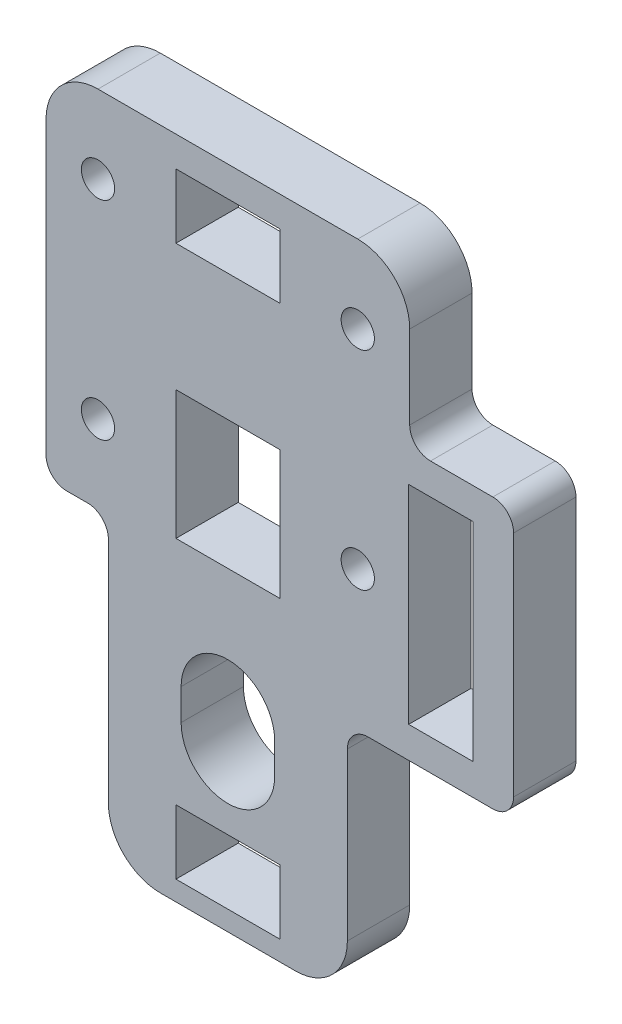
SolidWorks part; units mm, degrees
ref_plane "Front Plane" through (0, 0, 0) normal (0, 0, 1) x (1, 0, 0)
ref_plane "Top Plane" through (0, 0, 0) normal (0, 1, 0) x (1, 0, 0)
ref_plane "Right Plane" through (0, 0, 0) normal (1, 0, 0) x (0, 0, -1)
sketch "Sketch1" plane through (0, 0, 0) normal (0, 0, 1) x (1, 0, 0)
  line L0 (-5, -6.3) -> (5, -6.3)
  line L1 (-12.5, -12.5) -> (12.5, -12.5) construction
  line L2 (-12.5, -12.5) -> (-12.5, 7.5) construction
  line L3 (-12.5, 7.5) -> (12.5, 7.5) construction
  line L4 (12.5, -12.5) -> (12.5, 7.5) construction
  line L5 (-12.5, -12.5) -> (12.5, 7.5) construction
  line L6 (-12.5, 7.5) -> (12.5, -12.5) construction
  line L7 (17.5, -20) -> (11.5, -20)
  line L8 (17.5, -20) -> (17.5, 15)
  line L9 (17.5, 15) -> (-17.5, 15)
  line L10 (-17.5, -20) -> (-17.5, 15)
  line L11 (17.5, -20) -> (-17.5, 15) construction
  line L12 (17.5, 15) -> (-17.5, -20) construction
  line L13 (-5, 12.1) -> (5, 12.1)
  line L14 (-5, 12.1) -> (-5, 5.9)
  line L15 (-5, 5.9) -> (5, 5.9)
  line L16 (5, 12.1) -> (5, 5.9)
  line L17 (-5, 12.1) -> (5, 5.9) construction
  line L18 (-5, 5.9) -> (5, 12.1) construction
  line L19 (-5, -6.3) -> (-5, -18.7)
  line L20 (-5, -18.7) -> (5, -18.7)
  line L21 (5, -6.3) -> (5, -18.7)
  line L22 (-5, -6.3) -> (5, -18.7) construction
  line L23 (-5, -18.7) -> (5, -6.3) construction
  line L24 (0, 24.9943) -> (0, -49) construction
  line L25 (-11.5, -20) -> (-17.5, -20)
  line L26 (-11.5, -49) -> (11.5, -49)
  line L27 (-11.5, -49) -> (-11.5, -20)
  line L29 (11.5, -49) -> (11.5, -20)
  line L30 (-11.5, -49) -> (11.5, -20) construction
  line L31 (-11.5, -20) -> (11.5, -49) construction
  line L32 (0, -33.8) -> (0, -30.8) construction
  line L33 (-4.5, -33.8) -> (-4.5, -30.8)
  line L34 (4.5, -33.8) -> (4.5, -30.8)
  line L35 (-5, -40.9) -> (5, -40.9)
  line L36 (-5, -40.9) -> (-5, -47.1)
  line L37 (-5, -47.1) -> (5, -47.1)
  line L38 (5, -40.9) -> (5, -47.1)
  line L39 (-5, -40.9) -> (5, -47.1) construction
  line L40 (-5, -47.1) -> (5, -40.9) construction
  circle A0 centre (12.5, 7.5) radius 1.6
  circle A1 centre (-12.5, 7.5) radius 1.6
  circle A2 centre (-12.5, -12.5) radius 1.6
  circle A3 centre (12.5, -12.5) radius 1.6
  arc A4 (-4.5, -33.8) -> (4.5, -33.8) centre (0, -33.8) ccw
  arc A5 (4.5, -30.8) -> (-4.5, -30.8) centre (0, -30.8) ccw
  point P0 (0, -2.5)
  point P7 (0, 9)
  point P9 (0, -2.5)
  point P24 (0, -12.5)
  point P29 (0, -32.3)
  point P31 (0, -34.5)
  point P46 (0, -44)
  dimension "D3" = 3.2
  dimension "D15" = 4.5
  dimension "D1" = 25
  dimension "D2" = 20
  dimension "D4" = 35
  dimension "D5" = 35
  dimension "D6" = 6
  dimension "D7" = 10
  dimension "D8" = 6.2
  dimension "D9" = 10
  dimension "D10" = 12.4
  dimension "D12" = 23
  dimension "D13" = 29
  dimension "D14" = 47.3
  dimension "D16" = 3
  dimension "D17" = 10
  dimension "D18" = 6.2
  dimension "D19" = 5
extrude "Boss-Extrude1" add sketch "Sketch1" along normal blind 6
sketch "Sketch4" plane through (17.5, 0, 0) normal (1, 0, 0) x (0, 0, -1)
  line L0 (0, 0) -> (-6, 0)
  line L4 (0, -20) -> (0, 15)
  line L5 (0, 15) -> (-6, 15)
  line L6 (-6, 15) -> (-6, -20)
  line L7 (-6, -20) -> (0, -20)
  line L8 (0, -20) -> (0, 0)
  line L10 (-6, 0) -> (-6, -20)
  line L11 (-6, -20) -> (0, -20)
  dimension "D2" = 20
  dimension "D1" = 0
extrude "Boss-Extrude2" add sketch "Sketch4" along normal blind 10
sketch "Sketch7" plane through (11.5, 0, 0) normal (1, 0, 0) x (0, 0, -1)
  line L0 (-6, -26) -> (0, -26)
  line L1 (-6, -49) -> (-6, -20) construction
  line L2 (0, -49) -> (0, -20) construction
  line L7 (-6, -20) -> (-6, -49)
  line L8 (-6, -49) -> (0, -49)
  line L9 (0, -49) -> (0, -20)
  line L10 (0, -20) -> (-6, -20)
  line L11 (-6, -20) -> (-6, -26)
  line L13 (0, -26) -> (0, -20)
  line L14 (0, -20) -> (-6, -20)
  line L15 (-6, -49) -> (0, -49)
  line M6 (-6, -20) -> (-6, -49)
  line M8 (0, -49) -> (0, -20)
  line M9 (0, -20) -> (-6, -20)
  dimension "D2" = 6
  dimension "D1" = 0
extrude "Boss-Extrude3" add sketch "Sketch7" along normal up to surface (16 mm away) contours L0 M6 M8 M9 up to face at (27.5, -10, 3)
sketch "Sketch6" plane through (0, 0, 6) normal (0, 0, 1) x (1, 0, 0)
  line L0 (27.5, -13) -> (-17.5, -13) construction
  line L1 (17.4, -3) -> (23.6, -3)
  line L2 (17.4, -3) -> (17.4, -23)
  line L3 (17.4, -23) -> (23.6, -23)
  line L4 (23.6, -3) -> (23.6, -23)
  line L5 (17.4, -3) -> (23.6, -23) construction
  line L6 (17.4, -23) -> (23.6, -3) construction
  line L7 (27.5, 0) -> (27.5, -26) construction
  line L8 (-17.5, 15) -> (-17.5, -20) construction
  line L10 (12.5, 7.5) -> (12.5, -12.5) construction
  point P0 (20.5, -13)
  point P11 (0, 0)
  point P16 (0, 0)
  point P17 (0, 0)
  point P18 (0, 0)
  point P19 (0, 0)
  point P20 (0, 0)
  dimension "D1" = 6.2
  dimension "D2" = 20
  dimension "D3" = 8
extrude "Cut-Extrude1" cut sketch "Sketch6" against normal up to next
fillet "Fillet1" radius 2 6 edges at (-11.5, -20, 3) (-17.5, -20, 3) (17.5, 0, 3) (11.5, -26, 3) (27.5, -26, 3) (27.5, 0, 3)
fillet "Fillet2" radius 5 4 edges at (17.5, 15, 3) (-17.5, 15, 3) (-11.5, -49, 3) (11.5, -49, 3)
